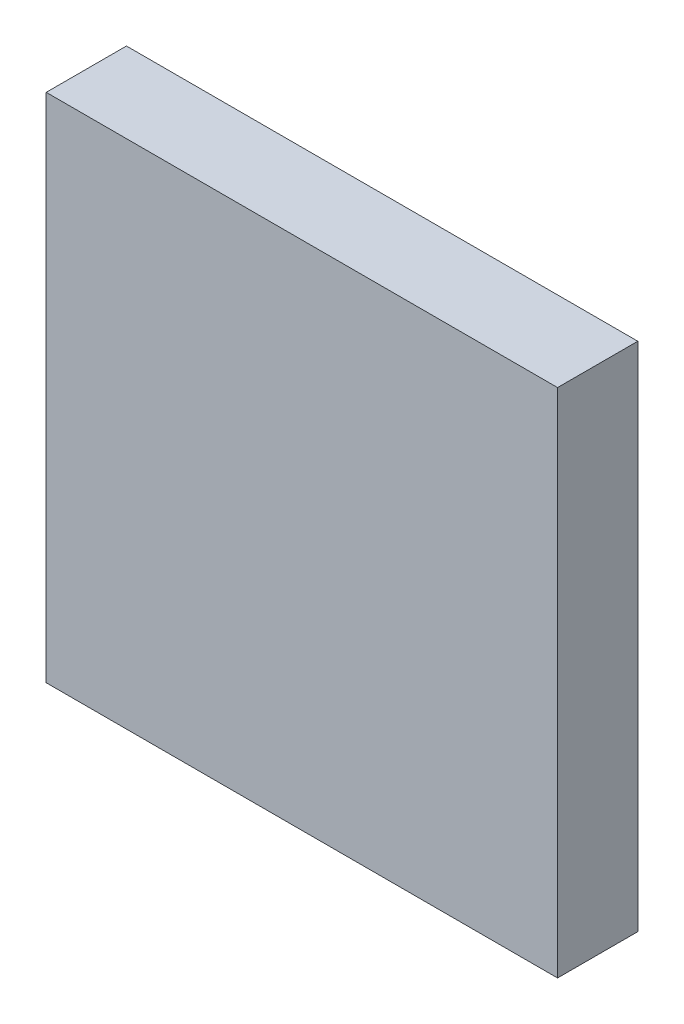
SolidWorks part; units mm, degrees
ref_plane "Front Plane" through (0, 0, 0) normal (0, 0, 1) x (1, 0, 0)
ref_plane "Top Plane" through (0, 0, 0) normal (0, 1, 0) x (1, 0, 0)
ref_plane "Right Plane" through (0, 0, 0) normal (1, 0, 0) x (0, 0, -1)
sketch "Sketch1" plane through (0, 0, 0) normal (0, 0, 1) x (1, 0, 0)
  line L0 (24.4629, 27.7853) -> (-35.5371, 27.7853) construction
  line L1 (-35.5371, 27.7853) -> (-35.5371, -32.2147) construction
  line L2 (-35.5371, -32.2147) -> (24.4629, -32.2147) construction
  line L3 (24.4629, -32.2147) -> (24.4629, 27.7853) construction
  line L4 (24.4629, 27.7853) -> (-35.5371, 27.7853) construction
  line L5 (-35.5371, 27.7853) -> (-35.5371, -32.2147) construction
  line L6 (-35.5371, -32.2147) -> (24.4629, -32.2147) construction
  line L7 (24.4629, -32.2147) -> (24.4629, 27.7853) construction
  line L8 (26.9629, 30.2853) -> (-38.0371, 30.2853)
  line L9 (-38.0371, 30.2853) -> (-38.0371, -34.7147)
  line L10 (-38.0371, -34.7147) -> (26.9629, -34.7147)
  line L11 (26.9629, -34.7147) -> (26.9629, 30.2853)
  dimension "D1" = 2.5
extrude "Boss-Extrude1" add sketch "Sketch1" along normal blind 9 contours L8 L9 L10 L11
sketch "Sketch2" plane through (0, 0, 0) normal (0, 0, -1) x (-1, 0, 0)
  line L0 (-24.4629, -32.2147) -> (-24.4629, 27.7853) construction
  line L1 (-24.4629, 27.7853) -> (35.5371, 27.7853) construction
  line L2 (35.5371, 27.7853) -> (35.5371, -32.2147) construction
  line L3 (35.5371, -32.2147) -> (-24.4629, -32.2147) construction
  line L4 (-24.4629, -32.2147) -> (-24.4629, 27.7853) construction
  line L5 (-24.4629, 27.7853) -> (35.5371, 27.7853) construction
  line L6 (35.5371, 27.7853) -> (35.5371, -32.2147) construction
  line L7 (35.5371, -32.2147) -> (-24.4629, -32.2147) construction
  line L8 (-24.5629, -32.3147) -> (-24.5629, 27.8853)
  line L9 (-24.5629, 27.8853) -> (35.6371, 27.8853)
  line L10 (35.6371, 27.8853) -> (35.6371, -32.3147)
  line L11 (35.6371, -32.3147) -> (-24.5629, -32.3147)
  line L12 (-26.9629, 30.2853) -> (38.0371, 30.2853) construction
  line L13 (-26.9629, -34.7147) -> (-26.9629, 30.2853) construction
  line L14 (38.0371, -34.7147) -> (-26.9629, -34.7147) construction
  line L15 (38.0371, 30.2853) -> (38.0371, -34.7147) construction
  line L16 (-26.9629, 30.2853) -> (38.0371, 30.2853)
  line L17 (-26.9629, -34.7147) -> (-26.9629, 30.2853)
  line L18 (38.0371, -34.7147) -> (-26.9629, -34.7147)
  line L19 (38.0371, 30.2853) -> (38.0371, -34.7147)
  dimension "D1" = 0.1
extrude "Boss-Extrude2" add sketch "Sketch2" along normal blind 1.2
sketch "Sketch3" plane through (0, 0, 0) normal (0, 0, -1) x (-1, 0, 0)
  line L0 (35.6371, 27.8853) -> (-24.5629, 27.8853) construction
  line L1 (35.6371, -32.3147) -> (35.6371, 27.8853) construction
  line L2 (-24.5629, -32.3147) -> (35.6371, -32.3147) construction
  line L3 (-24.5629, 27.8853) -> (-24.5629, -32.3147) construction
  line L4 (35.6371, 27.8853) -> (-24.5629, 27.8853) construction
  line L5 (35.6371, -32.3147) -> (35.6371, 27.8853) construction
  line L6 (-24.5629, -32.3147) -> (35.6371, -32.3147) construction
  line L7 (-24.5629, 27.8853) -> (-24.5629, -32.3147) construction
  line L8 (32.0121, 24.2603) -> (-20.9379, 24.2603)
  line L9 (-20.9379, 24.2603) -> (-20.9379, -28.6897)
  line L10 (-20.9379, -28.6897) -> (32.0121, -28.6897)
  line L11 (32.0121, -28.6897) -> (32.0121, 24.2603)
  dimension "D1" = 3.625
extrude "Cut-Extrude1" cut sketch "Sketch3" against normal offset from surface (8 mm away) 1 up to face at (-5.5371, -2.2147, 9)
sketch "Sketch4" plane through (-38.0371, 0, 0) normal (-1, 0, 0) x (0, 0, 1)
  line L0 (0, 27.3803) -> (0, -34.3204) construction
  text T0 "dist=8,thick=1"
extrude "Cut-Extrude2" cut sketch "Sketch4" against normal blind 0.5
